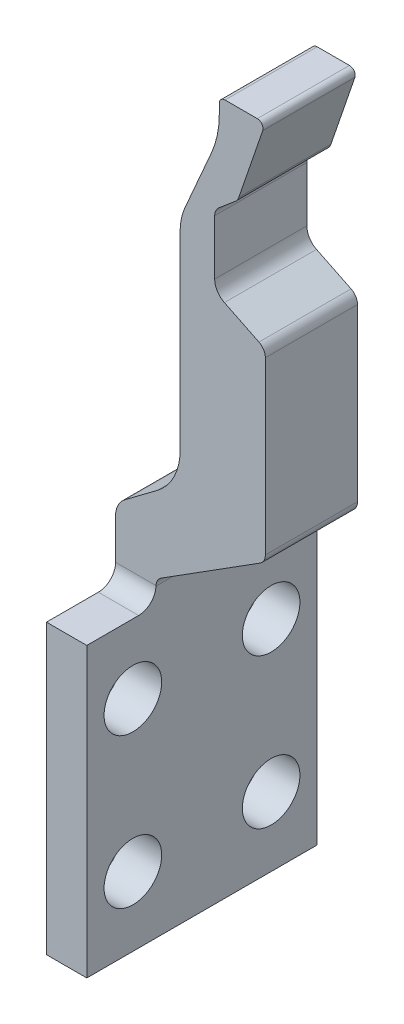
SolidWorks part; units mm, degrees
material "1060 Alloy"
ref_plane "Front Plane" through (0, 0, 0) normal (0, 0, 1) x (1, 0, 0)
ref_plane "Top Plane" through (0, 0, 0) normal (0, 1, 0) x (1, 0, 0)
ref_plane "Right Plane" through (0, 0, 0) normal (1, 0, 0) x (0, 0, -1)
sketch "Sketch1" plane through (0, 0, 0) normal (1, 0, 0) x (0, 0, -1)
  line L1 (0, 0) -> (20, 0)
  line L2 (0, 0) -> (0, 25)
  line L3 (0, 25) -> (20, 25)
  line L4 (20, 0) -> (20, 25)
  line L5 (6, 25) -> (14, 25)
  line L6 (6, 25) -> (6, 66)
  line L7 (6, 66) -> (14, 66)
  line L8 (14, 25) -> (14, 66)
  dimension "D1" = 25
  dimension "D2" = 20
  dimension "D3" = 8
  dimension "D4" = 6
  dimension "D5" = 41
extrude "Boss-Extrude2" add sketch "Sketch1" along normal blind 3.5 contours L1 L4 L3 L2
sketch "Sketch2" plane through (3.5, 0, 0) normal (1, 0, 0) x (0, 0, -1)
  line L0 (0, 25) -> (20, 25) construction
  line L1 (6, 25) -> (14, 25)
  line L2 (6, 25) -> (6, 66)
  line L3 (6, 66) -> (14, 66)
  line L4 (14, 25) -> (14, 66)
  line L5 (20, 0) -> (20, 25) construction
  dimension "D1" = 6
  dimension "D2" = 41
  dimension "D3" = 8
extrude "Boss-Extrude3" add sketch "Sketch2" along normal blind 9.5 and the other way blind 3.5
sketch "Sketch3" plane through (0, 0, 0) normal (-1, 0, 0) x (0, 0, 1)
  line L0 (-4, 25) -> (-4, 19) construction
  line L1 (0, 25) -> (-6, 25) construction
  line L2 (-4, 19) -> (0, 19) construction
  line L3 (0, 0) -> (0, 25) construction
  line L4 (-20, 19) -> (-16, 19) construction
  line L5 (-20, 0) -> (-20, 25) construction
  line L6 (-16, 19) -> (-16, 25) construction
  line L7 (-14, 25) -> (-20, 25) construction
  line L8 (-20, 6) -> (-16, 6) construction
  line L9 (-16, 6) -> (-16, 0) construction
  line L10 (0, 0) -> (-20, 0) construction
  line L11 (-4, 0) -> (-4, 6) construction
  line L12 (-4, 6) -> (0, 6) construction
  circle A0 centre (-16, 19) radius 2.5
  circle A1 centre (-16, 6) radius 2.5
  circle A2 centre (-4, 6) radius 2.5
  circle A3 centre (-4, 19) radius 2.5
  dimension "D8" = 5
  dimension "D9" = 5
  dimension "D10" = 5
  dimension "D11" = 5
  dimension "D1" = 6
  dimension "D2" = 4
  dimension "D3" = 4
  dimension "D4" = 4
  dimension "D5" = 6
  dimension "D6" = 6
  dimension "D7" = 4
extrude "Cut-Extrude1" cut sketch "Sketch3" against normal blind 9.5
sketch "Sketch4" plane through (0, 0, -6) normal (0, 0, 1) x (1, 0, 0)
  line L0 (0, 25) -> (0, 31)
  line L1 (0, 66) -> (0, 25) construction
  line L2 (0, 31) -> (5.6005, 35.1994)
  line L3 (5.6005, 35.1994) -> (5.6005, 55.1994)
  line L5 (0, 66) -> (13, 66) construction
  line L6 (13, 49) -> (8.6005, 51.1531)
  line L7 (8.6005, 51.1531) -> (8.6005, 57.3182)
  line L8 (8.6005, 57.3182) -> (10.6005, 59.0091)
  line L9 (10.6005, 59.0091) -> (13, 66)
  line L10 (13, 66) -> (13, 25) construction
  line L11 (13, 49) -> (13, 33)
  line L12 (13, 33) -> (3.5, 27)
  line L13 (3.5, 27) -> (3.5, 25)
  line L14 (0, 25) -> (3.5, 25) construction
  line L15 (9, 66) -> (9, 63)
  line L16 (9, 63) -> (5.6005, 55.1994)
  line L17 (13, 66) -> (9, 66)
  line L19 (0, 25) -> (3.5, 25)
  line L20 (3.5, 25) -> (13, 25)
  line L21 (13, 25) -> (13, 33)
  line L22 (13, 49) -> (13, 66)
  line L23 (9, 66) -> (0, 66)
  line L24 (0, 66) -> (0, 31)
  line M12 (3.5, 25) -> (13, 25)
  line M13 (13, 25) -> (13, 66)
  line M14 (13, 66) -> (0, 66)
  line M15 (0, 66) -> (0, 25)
  dimension "D1" = 6
  dimension "D2" = 3
  dimension "D3" = 16
  dimension "D4" = 2
  dimension "D5" = 8
  dimension "D6" = 20
  dimension "D7" = 7
  dimension "D8" = 2
  dimension "D9" = 3.5
  dimension "D12" = 3
extrude "Cut-Extrude2" cut sketch "Sketch4" against normal blind 9.5 contours L16 L15 L2 L3 M14 M15 | L12 L13 M12 M13 | L9 L8 L7 L6 M13
fillet "Fillet1" radius 1.5 1 edges at (1.75, 25, -6)
fillet "Fillet2" radius 1.5 1 edges at (1.75, 25, -14)
fillet "Fillet3" radius 2 1 edges at (0, 31, -10)
fillet "Fillet4" radius 5 1 edges at (5.6005, 35.1994, -10)
fillet "Fillet5" radius 5 1 edges at (5.6005, 55.1994, -10)
fillet "Fillet6" radius 8 1 edges at (9, 63, -10)
fillet "Fillet7" radius 0.5 1 edges at (9, 66, -10)
fillet "Fillet8" radius 1 1 edges at (3.5, 27, -10)
fillet "Fillet9" radius 1 1 edges at (13, 33, -10)
fillet "Fillet10" radius 1 1 edges at (13, 49, -10)
fillet "Fillet11" radius 1.5 1 edges at (8.6005, 51.1531, -10)
fillet "Fillet12" radius 1 1 edges at (8.6005, 57.3182, -10)
fillet "Fillet13" radius 1 1 edges at (10.6005, 59.0091, -10)
fillet "Fillet14" radius 0.5 1 edges at (13, 66, -10)
